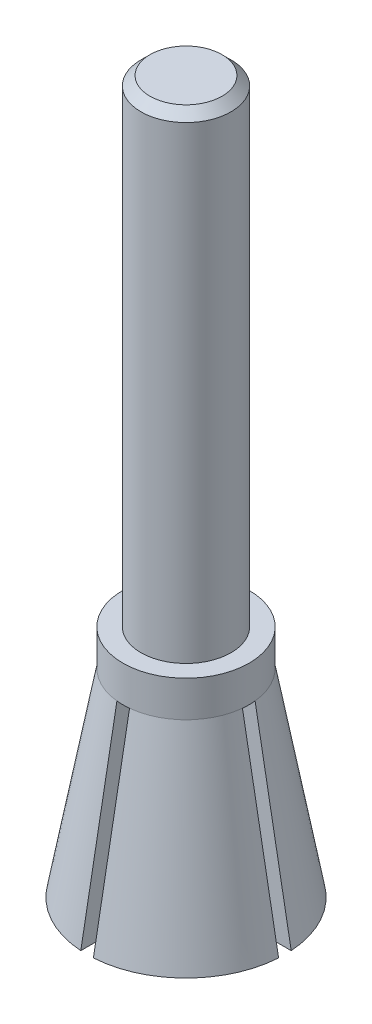
SolidWorks part; units mm, degrees
ref_plane "Front Plane" through (0, 0, 0) normal (0, 0, 1) x (1, 0, 0)
ref_plane "Top Plane" through (0, 0, 0) normal (0, 1, 0) x (1, 0, 0)
ref_plane "Right Plane" through (0, 0, 0) normal (1, 0, 0) x (0, 0, -1)
sketch "Sketch1" plane through (0, 0, 0) normal (0, 1, 0) x (1, 0, 0)
  circle A0 centre (0, 0) radius 5.5
  dimension "D1" = 11
extrude "Boss-Extrude1" add sketch "Sketch1" along normal blind 11 draft 10.3
sketch "Sketch2" plane through (0, 11, 0) normal (0, 1, 0) x (1, 0, 0)
  circle A1 centre (0, 0) radius 3.501
  circle A2 centre (0, 0) radius 3.501
  dimension "D1" = 0
extrude "Boss-Extrude2" add sketch "Sketch2" along normal blind 2
sketch "Sketch3" plane through (0, 13, 0) normal (0, 1, 0) x (1, 0, 0)
  circle A0 centre (0, 0) radius 2.5
  dimension "D1" = 5
extrude "Boss-Extrude3" add sketch "Sketch3" along normal blind 26.5
chamfer "Chamfer1" distance 0.5 angle 45 1 edges at (0, 39.5, 2.5)
sketch "Sketch4" plane through (0, 0, 0) normal (0, -1, 0) x (1, 0, 0)
  line L0 (0, 0) -> (0, 5.5) construction
  line L1 (0.35, 5.4889) -> (0.35, 1.9691)
  line L2 (-0.35, 5.4889) -> (-0.35, 1.9691)
  line L3 (5.4889, 0.35) -> (1.9691, 0.35)
  line L4 (5.4889, -0.35) -> (1.9691, -0.35)
  line L5 (0.35, -5.4889) -> (0.35, -1.9691)
  line L6 (-0.35, -5.4889) -> (-0.35, -1.9691)
  line L7 (-5.4889, -0.35) -> (-1.9691, -0.35)
  line L8 (-5.4889, 0.35) -> (-1.9691, 0.35)
  arc A0 (-0.35, 1.9691) -> (-1.9691, 0.35) centre (0, 0) ccw
  circle A1 centre (0, 0) radius 5.5 construction
  arc A2 (0.35, 5.4889) -> (-0.35, 5.4889) centre (0, 0) ccw
  arc A3 (5.4889, -0.35) -> (5.4889, 0.35) centre (0, 0) ccw
  arc A4 (-0.35, -5.4889) -> (0.35, -5.4889) centre (0, 0) ccw
  arc A5 (-5.4889, 0.35) -> (-5.4889, -0.35) centre (0, 0) ccw
  arc A6 (1.9691, 0.35) -> (0.35, 1.9691) centre (0, 0) ccw
  arc A7 (0.35, -1.9691) -> (1.9691, -0.35) centre (0, 0) ccw
  arc A8 (-1.9691, -0.35) -> (-0.35, -1.9691) centre (0, 0) ccw
  dimension "D1" = 4
  dimension "D2" = 0.7
  dimension "D3" = 4
extrude "Cut-Extrude1" cut sketch "Sketch4" against normal blind 11
equation "\"。7\"=0.5"
